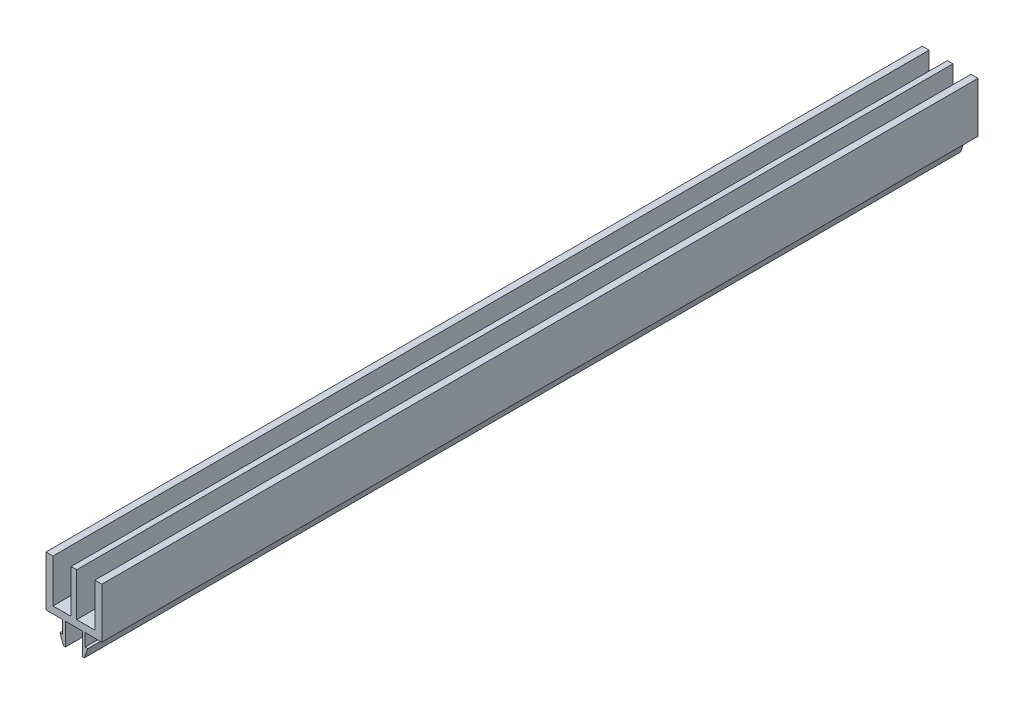
SolidWorks part; units mm, degrees
ref_plane "Plan de face" through (0, 0, 0) normal (0, 0, 1) x (1, 0, 0)
ref_plane "Plan de dessus" through (0, 0, 0) normal (0, 1, 0) x (1, 0, 0)
ref_plane "Plan de droite" through (0, 0, 0) normal (1, 0, 0) x (0, 0, -1)
ref_plane "Plan1" through (0, 0, 50) normal (0, 0, 1) x (1, 0, 0)
sketch "Esquisse1" plane through (0, 0, 50) normal (0, 0, 1) x (1, 0, 0)
  line L0 (-1, 2.5) -> (-7.5, 2.5)
  line L1 (-7.5, 2.5) -> (-7.5, 18)
  line L2 (-7.5, 18) -> (-10, 18)
  line L3 (-10, 18) -> (-10, 0)
  line L4 (-10, 0) -> (-4, 0)
  line L5 (-4, 0) -> (-4, -4.5)
  line L6 (-4, -4.5) -> (-5, -4.5)
  line L7 (-5, -4.5) -> (-3.75, -8)
  line L8 (-3.75, -8) -> (-3, -8)
  line L9 (-3, -8) -> (-3, 0)
  line L10 (-3, 0) -> (3, 0)
  line L11 (3, 0) -> (3, -8)
  line L12 (3, -8) -> (3.75, -8)
  line L13 (3.75, -8) -> (5, -4.5)
  line L14 (5, -4.5) -> (4, -4.5)
  line L15 (4, -4.5) -> (4, 0)
  line L16 (4, 0) -> (10, 0)
  line L17 (10, 0) -> (10, 18)
  line L18 (10, 18) -> (7.5, 18)
  line L19 (7.5, 18) -> (7.5, 2.5)
  line L20 (7.5, 2.5) -> (1, 2.5)
  line L21 (1, 2.5) -> (1, 18)
  line L22 (1, 18) -> (-1, 18)
  line L23 (-1, 18) -> (-1, 2.5)
extrude "Boss.-Extru.1" add sketch "Esquisse1" against normal blind 314
